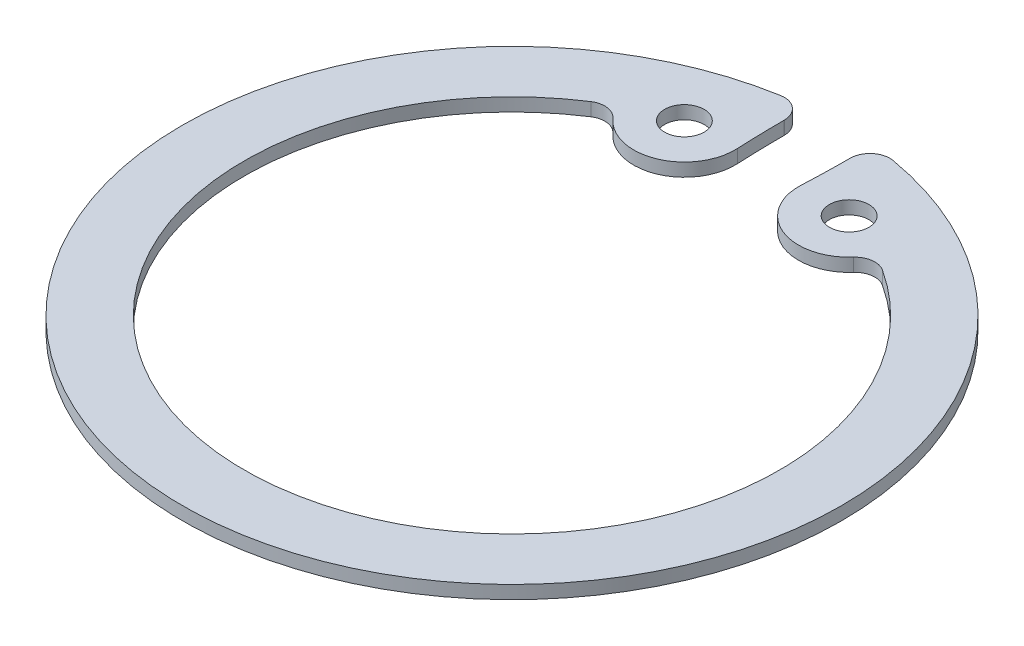
SolidWorks part; units mm, degrees
material "Brass"
ref_plane "Front Plane" through (0, 0, 0) normal (0, 0, 1) x (1, 0, 0)
ref_plane "Top Plane" through (0, 0, 0) normal (0, 1, 0) x (1, 0, 0)
ref_plane "Right Plane" through (0, 0, 0) normal (1, 0, 0) x (0, 0, -1)
sketch "Sketch1" plane through (0, 0, 0) normal (0, 1, 0) x (1, 0, 0)
  circle A0 centre (0, 0) radius 12.7
  circle A1 centre (0, 0) radius 10.3187
extrude "Boss-Extrude1" add sketch "Sketch1" along normal blind 0.508
sketch "Sketch2" plane through (0, 0.508, 0) normal (0, 1, 0) x (1, 0, 0)
  line L1 (-1.27, 9.1596) -> (1.27, 9.1596)
  line L2 (1.27, 9.1596) -> (1.27, 13.5249)
  line L3 (1.27, 13.5249) -> (-1.27, 13.5249)
  line L4 (-1.27, 13.5249) -> (-1.27, 9.1596)
extrude "Cut-Extrude1" cut sketch "Sketch2" against normal blind 0.508
fillet "Fillet1" radius 0.762 2 edges at (-1.27, 0.254, -12.6363) (1.27, 0.254, -12.6363)
sketch "Sketch3" plane through (0, 0.508, 0) normal (0, 1, 0) x (1, 0, 0)
  line L0 (0, 0) -> (0, 13.1896) construction
  line L1 (3.175, 7.7677) -> (3.175, 11.1171) construction
  line L2 (3.175, 7.7677) -> (0, 7.7677) construction
  line L3 (0, 7.7677) -> (-3.175, 7.7677) construction
  arc A2 (-1.27, 10.2403) -> (1.27, 10.2403) centre (0, 0) ccw construction
  arc A3 (1.27, 10.2403) -> (4.9665, 9.0449) centre (3.175, 9.8181) ccw
  arc A5 (1.27, 10.2403) -> (4.9665, 9.0449) centre (0, 0) cw
extrude "Boss-Extrude2" add sketch "Sketch3" against normal blind 0.508
sketch "Sketch4" plane through (0, 0.508, 0) normal (0, 1, 0) x (-1, 0, 0)
  circle A0 centre (-3.175, -9.8181) radius 0.762
extrude "Cut-Extrude2" cut sketch "Sketch4" against normal blind 0.508
sketch "Sketch5" plane through (0, 0, 0) normal (0, 1, 0) x (1, 0, 0)
  line L0 (0, 13.1227) -> (0, -13.6674)
  line L1 (0, -13.6674) -> (-16.6373, -10.4808)
  line L2 (-16.6373, -10.4808) -> (-17.786, 10.0843)
  line L3 (-17.786, 10.0843) -> (-7.7443, 13.7156)
  line L4 (-7.7443, 13.7156) -> (0, 13.1227)
extrude "Cut-Extrude4" cut sketch "Sketch5" against normal mid plane 25.4
fillet "Fillet2" radius 0.762 1 edges at (4.9665, 0.254, -9.0449)
fillet "Fillet3" radius 38.862 1 edges at (1.27, 0.254, -10.2403)
mirror "Mirror1" about plane through (0, 0, 0) normal (1, 0, 0) of bodies 105
